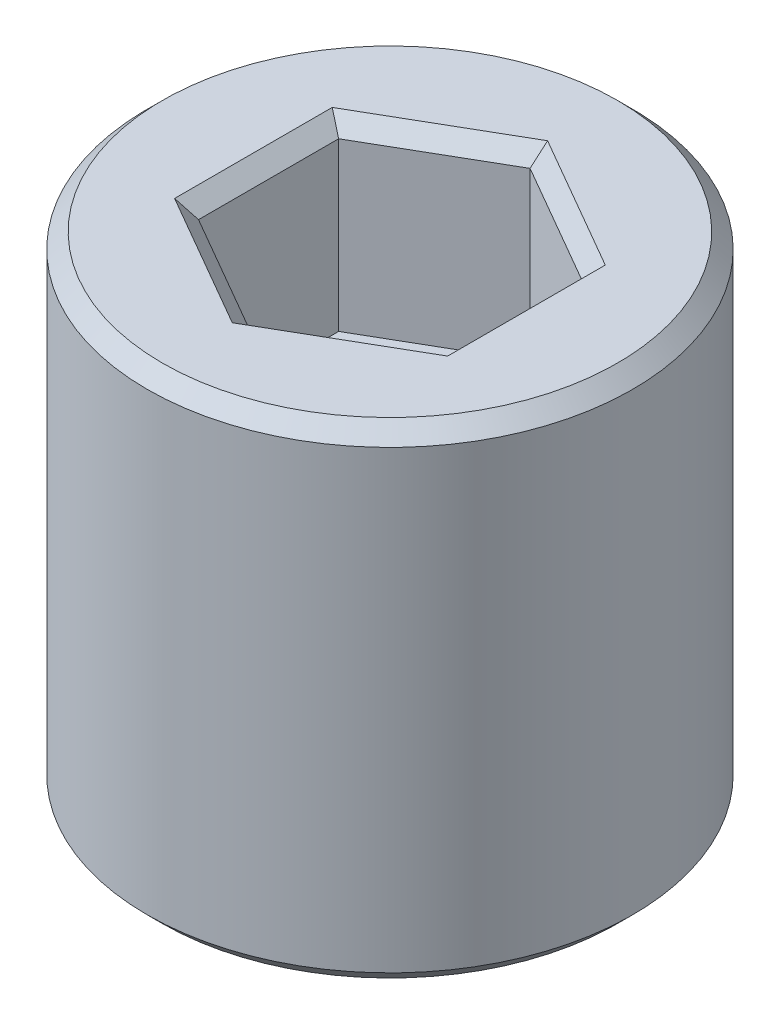
SolidWorks part; units mm, degrees
ref_plane "Front Plane" through (0, 0, 0) normal (0, 0, 1) x (1, 0, 0)
ref_plane "Top Plane" through (0, 0, 0) normal (0, 1, 0) x (1, 0, 0)
ref_plane "Right Plane" through (0, 0, 0) normal (1, 0, 0) x (0, 0, -1)
sketch "Sketch1" plane through (0, 0, 0) normal (0, 1, 0) x (1, 0, 0)
  circle A0 centre (0, 0) radius 4
  dimension "D1" = 8
extrude "Boss-Extrude1" add sketch "Sketch1" against normal blind 8
chamfer "Chamfer1" distance 0.25 2 edges at (0, 0, 4) (0, -8, 4)
cosmetic thread "Cosmetic Thread1" parameters "D2"=6.619
sketch "Sketch2" plane through (0, 0, 0) normal (0, 1, 0) x (1, 0, 0)
  line L0 (0, 2.3094) -> (2, 1.1547)
  line L1 (2, 1.1547) -> (2, -1.1547)
  line L2 (2, -1.1547) -> (0, -2.3094)
  line L3 (0, -2.3094) -> (-2, -1.1547)
  line L4 (-2, -1.1547) -> (-2, 1.1547)
  line L5 (-2, 1.1547) -> (0, 2.3094)
  circle A0 centre (0, 0) radius 2.3094 construction
  dimension "D1" = 4
extrude "Cut-Extrude1" cut sketch "Sketch2" against normal blind 3
chamfer "Chamfer2" distance 0.25 6 edges at (-1, 0, 1.7321) (1, 0, 1.7321) (2, 0, 0) (1, 0, -1.7321) (-1, 0, -1.7321) (-2, 0, 0)
